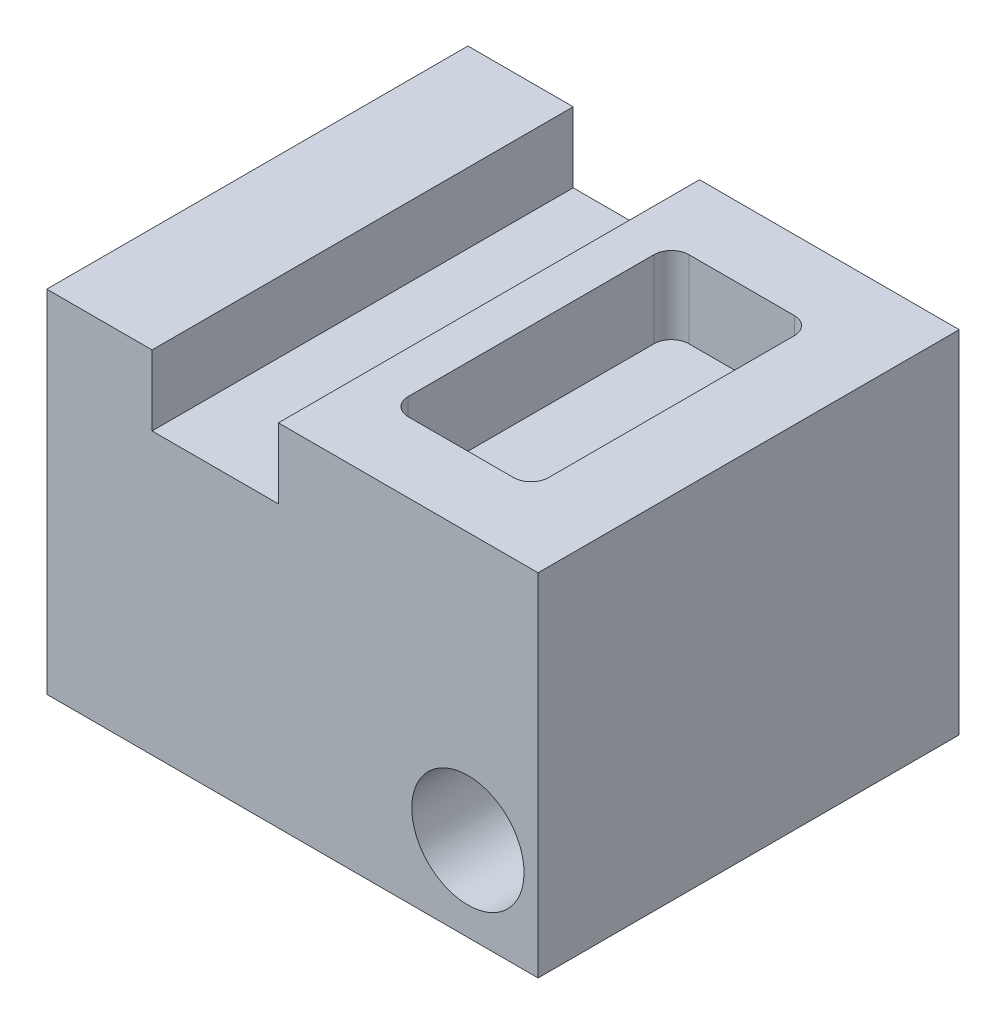
SolidWorks part; units mm, degrees
ref_plane "Plano frontal" through (0, 0, 0) normal (0, 0, 1) x (1, 0, 0)
ref_plane "Plano superior" through (0, 0, 0) normal (0, 1, 0) x (1, 0, 0)
ref_plane "Plano direito" through (0, 0, 0) normal (1, 0, 0) x (0, 0, -1)
sketch "Esboço7" plane through (0, 0, 0) normal (0, 0, 1) x (1, 0, 0)
  line L1 (0, 0) -> (70, 0)
  line L2 (0, 0) -> (0, 50)
  line L3 (0, 50) -> (70, 50)
  line L4 (70, 0) -> (70, 50)
extrude "Ressalto-extrusão3" add sketch "Esboço7" against normal blind 60
hole_wizard "Broca de rosquear para tarraxa de M1.2x0.252" positions "Esboço8" profile "Esboço9" hole size "M1.2x0.25" standard "Ansi Metric"
sketch "Esboço8" plane through (0, 0, 0) normal (0, 0, 1) x (1, 0, 0)
  point P0 (60, 12)
sketch "Esboço9" plane through (60, 12, 0) normal (1, 0, 0) x (0, -1, 0)
  line L0 (0, 0) -> (0, 22)
  line L1 (0, 22) -> (8, 22)
  line L2 (8, 22) -> (8, 0)
  line L5 (8, 0) -> (0, 0)
  line L10 (0, 22) -> (-8, 22) construction
  line L11 (0, -6.35) -> (0, 107.95) construction
  dimension "Hole Dia." = 16
  dimension "Hole Depth" = 22
  dimension "Drill Angle" = 180
sketch "Esboço11" plane through (0, 50, 0) normal (0, 1, 0) x (1, 0, 0)
  line L5 (41.5, 50) -> (56.5, 50)
  line L6 (39, 47.5) -> (39, 12.5)
  line L7 (41.5, 10) -> (56.5, 10)
  line L8 (59, 47.5) -> (59, 12.5)
  arc A0 (39, 12.5) -> (41.5, 10) centre (41.5, 12.5) ccw
  arc A1 (56.5, 10) -> (59, 12.5) centre (56.5, 12.5) ccw
  arc A2 (41.5, 50) -> (39, 47.5) centre (41.5, 47.5) ccw
  arc A3 (56.5, 50) -> (59, 47.5) centre (56.5, 47.5) cw
  dimension "D1" = 2.5
extrude "Corte-extrusão2" cut sketch "Esboço11" against normal blind 11
sketch "Esboço13" plane through (0, 0, 0) normal (0, 0, 1) x (1, 0, 0)
  line L0 (70, 50) -> (0, 50) construction
  line L1 (15, 50) -> (33, 50)
  line L2 (15, 50) -> (15, 40)
  line L3 (15, 40) -> (33, 40)
  line L4 (33, 50) -> (33, 40)
sketch "Esboço16" plane through (0, 50, 0) normal (0, 1, 0) x (1, 0, 0)
  line L0 (15, 0) -> (15, 60)
  line L1 (70, 60) -> (0, 60) construction
sweep "Varredura de corte1" cut profiles "Esboço13" path "Esboço16"
